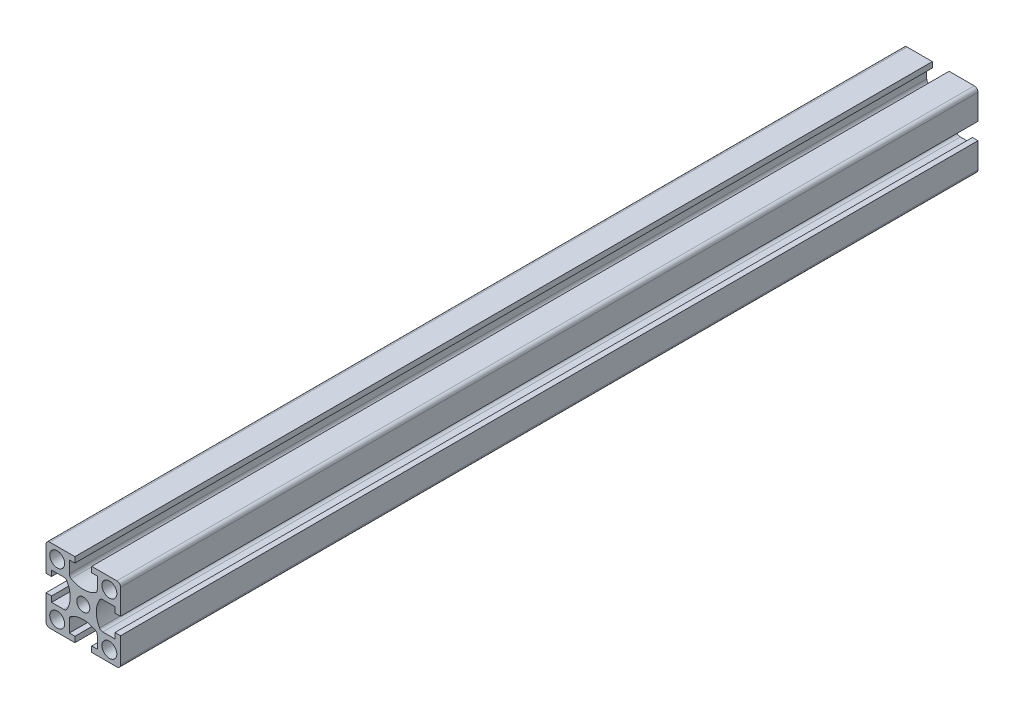
SolidWorks part; units mm, degrees
ref_plane "Front Plane" through (0, 0, 0) normal (0, 0, 1) x (1, 0, 0)
ref_plane "Top Plane" through (0, 0, 0) normal (0, 1, 0) x (1, 0, 0)
ref_plane "Right Plane" through (0, 0, 0) normal (1, 0, 0) x (0, 0, -1)
sketch "Sketch1" plane through (0, 0, 0) normal (0, 0, 1) x (1, 0, 0)
  line L64 (-20, 18) -> (-20, 4.5)
  line L65 (-20, 4.5) -> (-17, 4.5)
  line L66 (-17, 4.5) -> (-17, 7.5)
  line L67 (-17, 7.5) -> (-10.4737, 7.5)
  line L68 (-10.4737, -7.5) -> (-17, -7.5)
  line L69 (-17, -7.5) -> (-17, -4.5)
  line L70 (-17, -4.5) -> (-20, -4.5)
  line L71 (-20, -4.5) -> (-20, -18)
  line L72 (-18, -20) -> (-4.5, -20)
  line L73 (-4.5, -20) -> (-4.5, -17)
  line L74 (-4.5, -17) -> (-7.5, -17)
  line L75 (-7.5, -17) -> (-7.5, -10.4737)
  line L76 (7.5, -10.4737) -> (7.5, -17)
  line L77 (7.5, -17) -> (4.5, -17)
  line L78 (4.5, -17) -> (4.5, -20)
  line L79 (4.5, -20) -> (18, -20)
  line L80 (20, -18) -> (20, -4.5)
  line L81 (20, -4.5) -> (17, -4.5)
  line L82 (17, -4.5) -> (17, -7.5)
  line L83 (17, -7.5) -> (10.4737, -7.5)
  line L84 (10.4737, 7.5) -> (17, 7.5)
  line L85 (17, 7.5) -> (17, 4.5)
  line L86 (17, 4.5) -> (20, 4.5)
  line L87 (20, 4.5) -> (20, 18)
  line L88 (18, 20) -> (4.5, 20)
  line L89 (4.5, 20) -> (4.5, 17)
  line L90 (4.5, 17) -> (7.5, 17)
  line L91 (7.5, 17) -> (7.5, 10.4737)
  line L92 (-7.5, 10.4737) -> (-7.5, 17)
  line L93 (-7.5, 17) -> (-4.5, 17)
  line L94 (-4.5, 17) -> (-4.5, 20)
  line L95 (-4.5, 20) -> (-18, 20)
  circle A5 centre (-14, -14) radius 4
  circle A6 centre (14, -14) radius 4
  circle A7 centre (14, 14) radius 4
  circle A8 centre (0, 0) radius 3.5
  circle A9 centre (-14, 14) radius 4
  arc A32 (-18, 20) -> (-20, 18) centre (-18, 18) ccw
  arc A33 (-8.7417, 6.5) -> (-10.4737, 7.5) centre (-10.4737, 5.5) ccw
  arc A34 (-8.7417, -6.5) -> (-8.7417, 6.5) centre (-20, 0) ccw
  arc A35 (-10.4737, -7.5) -> (-8.7417, -6.5) centre (-10.4737, -5.5) ccw
  arc A36 (-20, -18) -> (-18, -20) centre (-18, -18) ccw
  arc A37 (-6.5, -8.7417) -> (-7.5, -10.4737) centre (-5.5, -10.4737) ccw
  arc A38 (6.5, -8.7417) -> (-6.5, -8.7417) centre (0, -20) ccw
  arc A39 (7.5, -10.4737) -> (6.5, -8.7417) centre (5.5, -10.4737) ccw
  arc A40 (18, -20) -> (20, -18) centre (18, -18) ccw
  arc A41 (8.7417, -6.5) -> (10.4737, -7.5) centre (10.4737, -5.5) ccw
  arc A42 (8.7417, 6.5) -> (8.7417, -6.5) centre (20, 0) ccw
  arc A43 (10.4737, 7.5) -> (8.7417, 6.5) centre (10.4737, 5.5) ccw
  arc A44 (20, 18) -> (18, 20) centre (18, 18) ccw
  arc A45 (6.5, 8.7417) -> (7.5, 10.4737) centre (5.5, 10.4737) ccw
  arc A46 (-6.5, 8.7417) -> (6.5, 8.7417) centre (0, 20) ccw
  arc A47 (-7.5, 10.4737) -> (-6.5, 8.7417) centre (-5.5, 10.4737) ccw
extrude "Boss-Extrude1" add sketch "Sketch1" along normal blind 460
